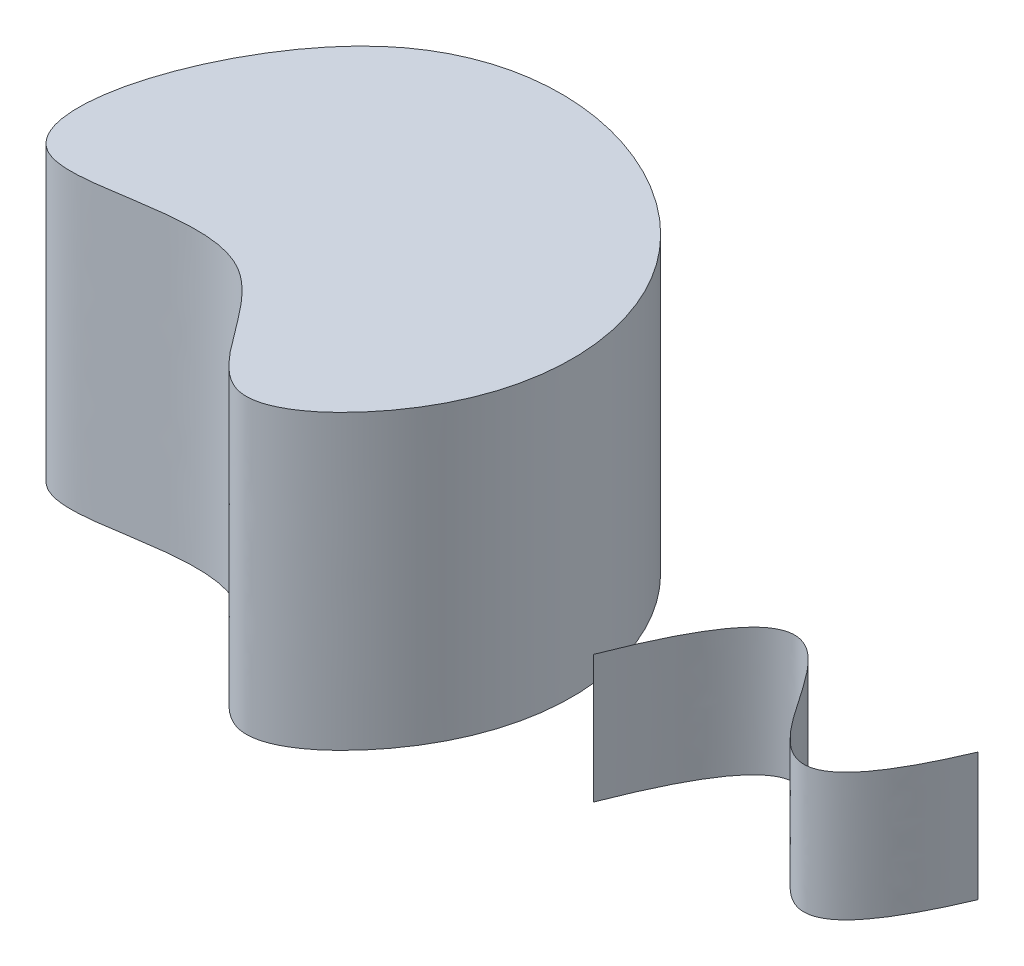
SolidWorks part; units mm, degrees
ref_plane "前视基准面" through (0, 0, 0) normal (0, 0, 1) x (1, 0, 0)
ref_plane "上视基准面" through (0, 0, 0) normal (0, 1, 0) x (1, 0, 0)
ref_plane "右视基准面" through (0, 0, 0) normal (1, 0, 0) x (0, 0, -1)
other "Configuration Table"
sketch "草图1" plane through (0, 0, 0) normal (0, 1, 0) x (1, 0, 0)
  spline S0 degree 3 poles (-66.7898, -21.4355) (26.3244, 217.5138) (37.2841, -160.0244) (127.9594, 54.3729) knots 0 0 0 0 1 1 1 1
surface "曲面-拉伸1" sketch "草图1" parameters "D1"=90
ref_plane "基准面1" through (0, 0, 110) normal (0, 0, 1) x (1, 0, 0)
sketch "草图2" plane through (0, 0, 110) normal (0, 0, 1) x (1, 0, 0)
  line L0 (-42.7946, 67.7153) -> (78.1311, 12.9313)
  line L1 (78.1311, 12.9313) -> (109.309, 56.135)
curve "曲线1"
sketch "草图3" plane through (0, 0, 110) normal (0, 0, 1) x (1, 0, 0)
  line L0 (-112.0541, 87.981) -> (107.3047, 8.9227)
curve "曲线2"
sketch "草图4" plane through (0, 0, 110) normal (0, 0, 1) x (1, 0, 0)
  line L1 (-33.9025, 67.7802) -> (76.7048, 67.7802)
  line L2 (-33.9025, 67.7802) -> (-33.9025, 20.2986)
  line L3 (-33.9025, 20.2986) -> (76.7048, 20.2986)
  line L4 (76.7048, 67.7802) -> (76.7048, 20.2986)
curve "曲线3"
sketch "草图5" plane through (0, 0, 0) normal (0, 1, 0) x (1, 0, 0)
  spline S0 degree 3 poles (-301.6586, 22.0457) (-513.009, -83.6551) (-412.464, 241.1691) (-142.2043, 170.7432) (-120.8971, -23.3128) (-249.3217, -139.7266) (-301.6586, 22.0457) (-513.009, -83.6551) (-412.464, 241.1691) knots -0.358553 -0.262625 -0.144898 0 0.206423 0.444935 0.641447 0.737375 0.855102 1 1.206423 1.444935 1.641447 only from (-448.1709, -23.412) to (-448.1709, -23.412)
  point P2 (-313.7687, -25.9164)
  point P4 (-235.2979, -101.8829)
extrude "凸台-拉伸1" add sketch "草图5" along normal blind 206
sketch "草图6" plane through (0, 0, 110) normal (0, 0, 1) x (1, 0, 0)
  line L0 (-414.3129, 86.6037) -> (-185.4475, 45.6129)
  line L1 (-480.5814, 175.7047) -> (-115.08, 134.7139)
curve "曲线4"
ref_plane "基准面2" through (0, 0, -110) normal (0, 0, 1) x (1, 0, 0)
sketch "草图7" plane through (0, 0, -110) normal (0, 0, 1) x (1, 0, 0)
  line L0 (-384.9362, 122.129) -> (-251.716, 103.6832)
curve "曲线5"
